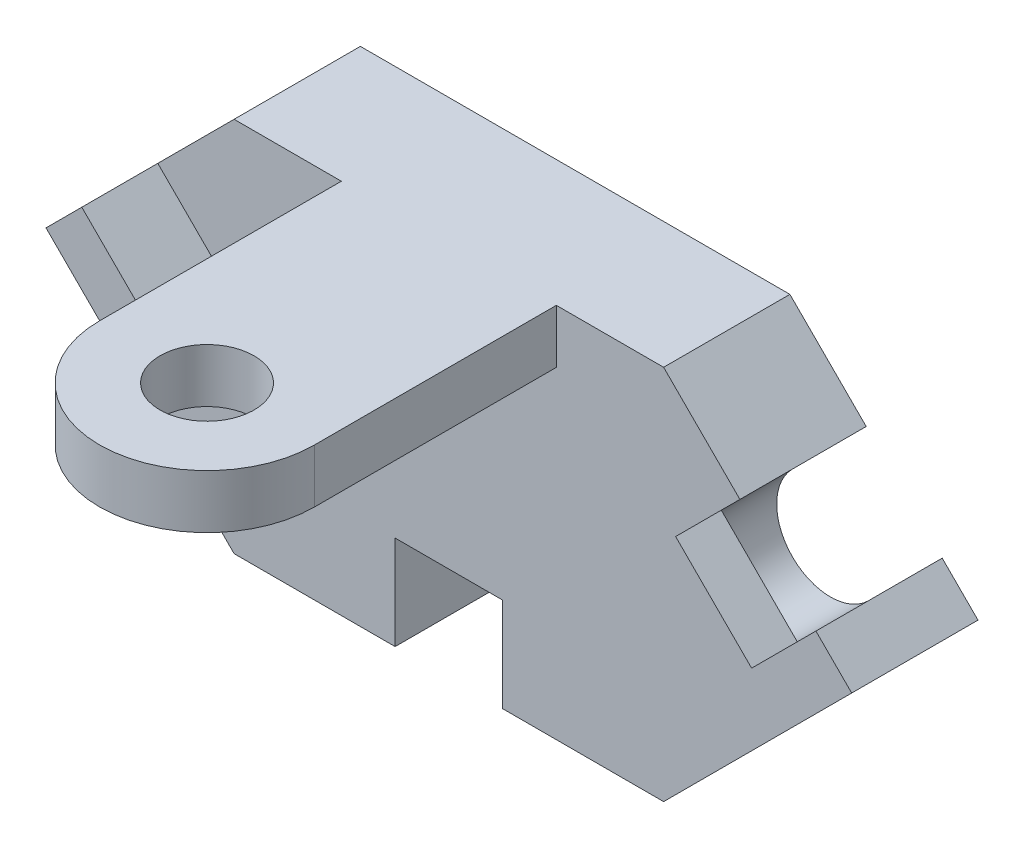
SolidWorks part; units mm, degrees
ref_plane "Plano frontal" through (0, 0, 0) normal (0, 0, 1) x (1, 0, 0)
ref_plane "Plano superior" through (0, 0, 0) normal (0, 1, 0) x (1, 0, 0)
ref_plane "Plano direito" through (0, 0, 0) normal (1, 0, 0) x (0, 0, -1)
sketch "Esboço1" plane through (0, 0, 0) normal (0, 0, 1) x (1, 0, 0)
  line L0 (-7.9929, 7) -> (-10.8322, 4.1607)
  line L1 (-14.9929, 0) -> (-7.9929, -7)
  line L2 (-7.9929, -7) -> (-2, -7)
  line L3 (7.9929, -7) -> (14.9929, 0)
  line L4 (14.9929, 0) -> (13.6607, 1.3322)
  line L5 (7.9929, 7) -> (-7.9929, 7)
  line L6 (0, 7) -> (0, -7) construction
  line L7 (-9.5, 0) -> (-12.2464, 2.7464) construction
  line L8 (9.5, 0) -> (12.3339, 2.8339) construction
  line L9 (-8.0858, 1.4142) -> (-10.8322, 4.1607)
  line L10 (10.9142, -1.4142) -> (13.6607, 1.3322)
  line L11 (-10.9142, -1.4142) -> (-13.6607, 1.3322)
  line L12 (8.0858, 1.4142) -> (10.8322, 4.1607)
  line L13 (-13.6607, 1.3322) -> (-14.9929, 0)
  line L14 (10.8322, 4.1607) -> (7.9929, 7)
  line L15 (-2, -3) -> (-2, -7)
  line L16 (2, -3) -> (2, -7)
  line L17 (2, -7) -> (7.9929, -7)
  arc A0 (-10.9142, -1.4142) -> (-8.0858, 1.4142) centre (-9.5, 0) ccw
  arc A1 (8.0858, 1.4142) -> (10.9142, -1.4142) centre (9.5, 0) ccw
  arc A2 (2, -3) -> (-2, -3) centre (0, -3) ccw
  dimension "D5" = 3
  dimension "D4" = 2
  dimension "D1" = 29.9858
  dimension "D2" = 14
  dimension "D3" = 19
extrude "Ressalto-extrusão1" add sketch "Esboço1" along normal blind 3
sketch "Esboço2" plane through (0, 0, 3) normal (0, 0, 1) x (1, 0, 0)
  line L0 (-11.2678, -1.0607) -> (-8.4393, 1.7678)
  line L1 (0, 7) -> (0, -7) construction
  line L2 (11.2678, -1.0607) -> (8.4393, 1.7678)
  line L3 (11.2678, -1.0607) -> (13.6607, 1.3322)
  line L4 (10.8322, 4.1607) -> (8.4393, 1.7678)
  line L5 (2, -3.5) -> (-2, -3.5)
  line L12 (7.9929, 7) -> (-7.9929, 7)
  line L13 (-7.9929, 7) -> (-10.8322, 4.1607)
  line L14 (-10.8322, 4.1607) -> (-8.0858, 1.4142)
  line L15 (-10.9142, -1.4142) -> (-13.6607, 1.3322)
  line L16 (-13.6607, 1.3322) -> (-14.9929, 0)
  line L17 (-14.9929, 0) -> (-7.9929, -7)
  line L18 (-7.9929, -7) -> (-2, -7)
  line L19 (7.9929, -7) -> (14.9929, 0)
  line L20 (14.9929, 0) -> (13.6607, 1.3322)
  line L21 (13.6607, 1.3322) -> (10.9142, -1.4142)
  line L22 (8.0858, 1.4142) -> (10.8322, 4.1607)
  line L23 (10.8322, 4.1607) -> (7.9929, 7)
  line L24 (7.9929, 7) -> (-7.9929, 7)
  line L25 (-7.9929, 7) -> (-10.8322, 4.1607)
  line L26 (-10.8322, 4.1607) -> (-8.4393, 1.7678)
  line L27 (-11.2678, -1.0607) -> (-13.6607, 1.3322)
  line L28 (-13.6607, 1.3322) -> (-14.9929, 0)
  line L29 (-14.9929, 0) -> (-7.9929, -7)
  line L30 (-7.9929, -7) -> (-2, -7)
  line L31 (7.9929, -7) -> (14.9929, 0)
  line L32 (14.9929, 0) -> (13.6607, 1.3322)
  line L35 (10.8322, 4.1607) -> (7.9929, 7)
  line L42 (-2, -7) -> (-2, -3)
  line L43 (-2, -7) -> (-2, -3.5)
  line L44 (2, -3) -> (2, -7)
  line L45 (2, -3.5) -> (2, -7)
  line L46 (2, -7) -> (7.9929, -7)
  line L47 (2, -7) -> (7.9929, -7)
  arc A2 (-10.9142, -1.4142) -> (-8.0858, 1.4142) centre (-9.5, 0) ccw
  arc A3 (8.0858, 1.4142) -> (10.9142, -1.4142) centre (9.5, 0) ccw
  arc A7 (2, -3) -> (-2, -3) centre (0, -3) ccw
  dimension "D2" = 0.5
  dimension "D3" = 0.5
  dimension "D1" = 0
extrude "Ressalto-extrusão2" add sketch "Esboço2" along normal blind 1.7
sketch "Esboço3" plane through (0, 7, 0) normal (0, 1, 0) x (1, 0, 0)
  line L1 (-7.9929, -2.35) -> (7.9929, -2.35) construction
  line L2 (7.9929, 0) -> (-7.9929, 0) construction
  line L3 (7.9929, -4.7) -> (-7.9929, -4.7) construction
  line L7 (-7.9929, -4.7) -> (-7.9929, 0) construction
  line L9 (7.9929, -4.7) -> (7.9929, 0) construction
  line L10 (-4, -4.7) -> (4, -13.7) construction
  line L11 (-4, -13.7) -> (4, -4.7) construction
  line L12 (4, -13.7) -> (4, -4.7)
  line L13 (-4, -4.7) -> (4, -4.7)
  line L14 (-4, -13.7) -> (-4, -4.7)
  circle A2 centre (0, -13.7) radius 1.75
  arc A3 (4, -13.7) -> (-4, -13.7) centre (0, -13.7) cw
  point P2 (0, 0)
  point P3 (0, -9.2)
  point P4 (4, -4.7)
  point P7 (-3.6821, -4.7)
  point P25 (0, -9.2)
  dimension "D3" = 13.7
  dimension "D1" = 4
  dimension "D2" = 3.5
  dimension "D4" = 8
extrude "Ressalto-extrusão3" add sketch "Esboço3" against normal blind 2
equation "\"D3@Esboço2\"=\"D2@Esboço2\""
